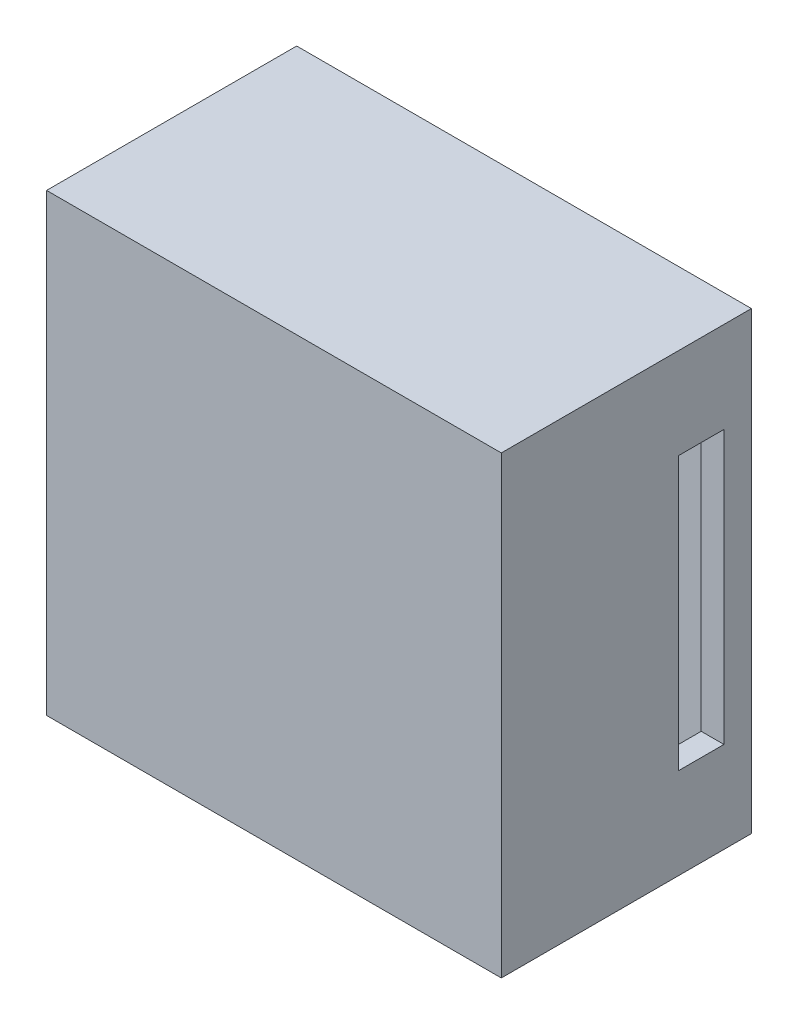
SolidWorks part; units mm, degrees
ref_plane "Front Plane" through (0, 0, 0) normal (0, 0, 1) x (1, 0, 0)
ref_plane "Top Plane" through (0, 0, 0) normal (0, 1, 0) x (1, 0, 0)
ref_plane "Right Plane" through (0, 0, 0) normal (1, 0, 0) x (0, 0, -1)
sketch "Sketch1" plane through (0, 0, 0) normal (0, 0, 1) x (1, 0, 0)
  line L1 (-50, -50) -> (50, -50)
  line L2 (-50, -50) -> (-50, 50)
  line L3 (-50, 50) -> (50, 50)
  line L4 (50, -50) -> (50, 50)
  line L5 (-50, -50) -> (50, 50) construction
  line L6 (-50, 50) -> (50, -50) construction
  point P0 (0, 0)
  dimension "D1" = 100
  dimension "D2" = 100
extrude "Boss-Extrude1" add sketch "Sketch1" along normal blind 50
shell "Shell1" thickness 5
sketch "Sketch2" plane through (50, 0, 0) normal (1, 0, 0) x (0, 0, -1)
  line L1 (-16.041, 30) -> (-6.041, 30)
  line L2 (-16.041, 30) -> (-16.041, -30)
  line L3 (-16.041, -30) -> (-6.041, -30)
  line L4 (-6.041, 30) -> (-6.041, -30)
  dimension "D1" = 10
  dimension "D2" = 60
extrude "Cut-Extrude1" cut sketch "Sketch2" against normal blind 19
sketch "Sketch3" plane through (0, 0, 50) normal (0, 0, 1) x (1, 0, 0)
  line L1 (-50, 50) -> (50, 50)
  line L2 (-50, 50) -> (-50, -50)
  line L3 (-50, -50) -> (50, -50)
  line L4 (50, 50) -> (50, -50)
extrude "Boss-Extrude2" add sketch "Sketch3" along normal blind 5
